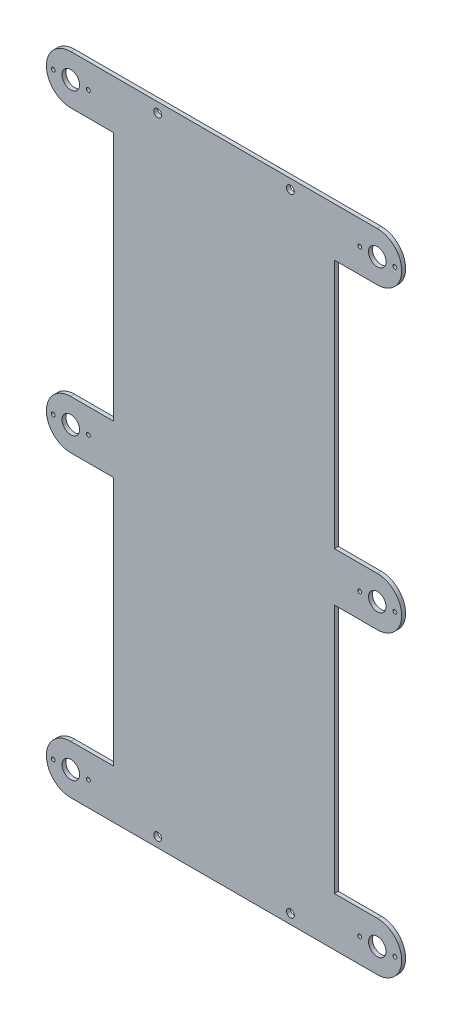
SolidWorks part; units mm, degrees
ref_plane "Plan de face" through (0, 0, 0) normal (0, 0, 1) x (1, 0, 0)
ref_plane "Plan de dessus" through (0, 0, 0) normal (0, 1, 0) x (1, 0, 0)
ref_plane "Plan de droite" through (0, 0, 0) normal (1, 0, 0) x (0, 0, -1)
sketch "Esquisse1" plane through (0, 0, 0) normal (0, 0, 1) x (1, 0, 0)
  line L0 (0, 192.3135) -> (0, -165.5) construction
  line L4 (-78.5, 165.5) -> (78.5, 165.5)
  line L5 (78.5, 140.5) -> (56.5, 140.5)
  line L6 (56.5, 140.5) -> (56.5, 12.5)
  line L7 (56.5, 12.5) -> (78.5, 12.5)
  line L8 (78.5, -12.5) -> (56.5, -12.5)
  line L9 (56.5, -12.5) -> (56.5, -140.5)
  line L10 (56.5, -140.5) -> (78.5, -140.5)
  line L12 (78.5, -165.5) -> (-78.5, -165.5)
  line L14 (78.5, 164.0039) -> (78.5, 114.0039) construction
  line L15 (78.5, 20.5695) -> (78.5, -29.4305) construction
  line L16 (78.5, -133.253) -> (78.5, -183.253) construction
  line L17 (96.5, 153) -> (56.5, 153) construction
  line L18 (84.5, 0) -> (44.5, 0) construction
  line L19 (56.5, -153) -> (96.5, -153) construction
  line L20 (0, 0) -> (237.8527, 0) construction
  line L21 (237.8527, 0) -> (-194.4576, 0) construction
  line L22 (-78.5, 164.0039) -> (-78.5, 114.0039) construction
  line L23 (-96.5, 153) -> (-56.5, 153) construction
  line L24 (-84.5, 0) -> (-44.5, 0) construction
  line L25 (-78.5, 20.5695) -> (-78.5, -29.4305) construction
  line L26 (-78.5, -133.253) -> (-78.5, -183.253) construction
  line L27 (-56.5, -153) -> (-96.5, -153) construction
  line L28 (-56.5, -140.5) -> (-78.5, -140.5)
  line L29 (-56.5, -12.5) -> (-56.5, -140.5)
  line L30 (-78.5, -12.5) -> (-56.5, -12.5)
  line L31 (-56.5, 12.5) -> (-78.5, 12.5)
  line L32 (-56.5, 140.5) -> (-56.5, 12.5)
  line L33 (-78.5, 140.5) -> (-56.5, 140.5)
  arc A1 (78.5, 165.5) -> (78.5, 140.5) centre (78.5, 153) cw
  arc A3 (78.5, 12.5) -> (78.5, -12.5) centre (78.5, 0) cw
  arc A5 (78.5, -140.5) -> (78.5, -165.5) centre (78.5, -153) cw
  circle A6 centre (78.5, 153) radius 4.5
  circle A7 centre (78.5, 0) radius 4.5
  circle A8 centre (78.5, -153) radius 4.5
  circle A9 centre (34, 160.5) radius 2
  circle A10 centre (69.5, 153) radius 1
  circle A11 centre (87.5, 153) radius 1
  circle A12 centre (69.5, 0) radius 1
  circle A13 centre (69.5, -153) radius 1
  circle A14 centre (87.5, 0) radius 1
  circle A15 centre (87.5, -153) radius 1
  circle A16 centre (34, -160.5) radius 2
  circle A17 centre (-78.5, 153) radius 4.5
  circle A18 centre (-87.5, 153) radius 1
  circle A19 centre (-69.5, 153) radius 1
  circle A20 centre (-34, 160.5) radius 2
  circle A21 centre (-87.5, 0) radius 1
  circle A22 centre (-78.5, 0) radius 4.5
  circle A23 centre (-69.5, 0) radius 1
  circle A24 centre (-87.5, -153) radius 1
  circle A25 centre (-69.5, -153) radius 1
  circle A26 centre (-78.5, -153) radius 4.5
  circle A27 centre (-34, -160.5) radius 2
  arc A28 (-78.5, -140.5) -> (-78.5, -165.5) centre (-78.5, -153) ccw
  arc A29 (-78.5, 12.5) -> (-78.5, -12.5) centre (-78.5, 0) ccw
  arc A30 (-78.5, 165.5) -> (-78.5, 140.5) centre (-78.5, 153) ccw
  point P34 (91, 153)
  point P35 (91, -153)
  point P97 (0, 165.5)
  dimension "D15" = 9
  dimension "D16" = 9
  dimension "D17" = 9
  dimension "D22" = 4
  dimension "D23" = 2
  dimension "D25" = 2
  dimension "D26" = 2
  dimension "D2" = 25
  dimension "D3" = 22
  dimension "D4" = 50
  dimension "D5" = 25
  dimension "D6" = 25
  dimension "D7" = 128
  dimension "D8" = 128
  dimension "D9" = 50
  dimension "D10" = 50
  dimension "D11" = 40
  dimension "D12" = 22
  dimension "D13" = 22
  dimension "D14" = 40
  dimension "D18" = 34
  dimension "D19" = 91
  dimension "D20" = 91
  dimension "D21" = 5
  dimension "D24" = 9
extrude "Boss.-Extru.1" add sketch "Esquisse1" along normal blind 2
